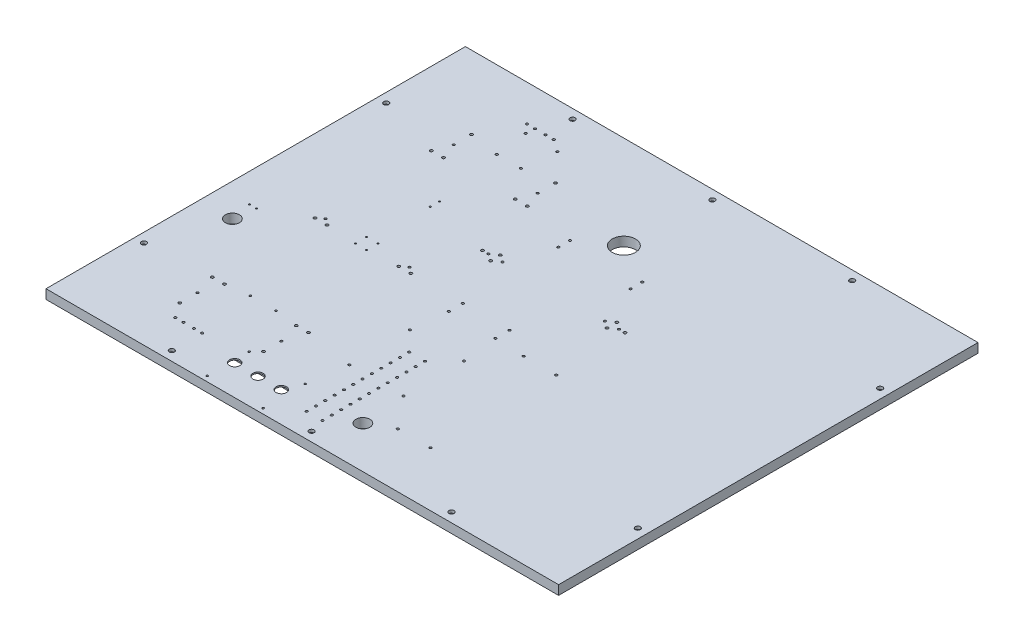
SolidWorks part; units mm, degrees
material "S45C表面镀硬铬"
ref_plane "前基準面" through (0, 0, 0) normal (0, 0, 1) x (1, 0, 0)
ref_plane "上基準面" through (0, 0, 0) normal (0, 1, 0) x (1, 0, 0)
ref_plane "右基準面" through (0, 0, 0) normal (1, 0, 0) x (0, 0, -1)
sketch "草图1" plane through (0, 0, 0) normal (0, 1, 0) x (1, 0, 0)
  line L1 (0, 0) -> (1100, 0)
  line L2 (0, 0) -> (0, 900)
  line L3 (0, 900) -> (1100, 900)
  line L4 (1100, 0) -> (1100, 900)
  dimension "D1" = 1100
  dimension "D2" = 900
extrude "凸台-拉伸1" add sketch "草图1" against normal blind 20
hole_wizard "M6 六角凹头螺钉的柱形沉头孔1" positions "草图3" profile "草图2" counterbore size "M6" standard "ISO" end condition through all
sketch "草图3" plane through (0, 0, 0) normal (0, 1, 0) x (-1, 0, 0)
  line L0 (0, -450) -> (-1100, -450) construction
  line L1 (0, -900) -> (0, 0) construction
  line L2 (-1100, 0) -> (-1100, -900) construction
  line L3 (-550, -900) -> (-550, 0) construction
  line L4 (-1100, -900) -> (0, -900) construction
  line L5 (0, 0) -> (-1100, 0) construction
  point P0 (-250, -20)
  point P1 (-550, -20)
  point P3 (-850, -20)
  point P5 (-1080, -190)
  point P7 (-1080, -710)
  point P9 (-850, -880)
  point P11 (-550, -880)
  point P13 (-250, -880)
  point P15 (-20, -710)
  point P17 (-20, -190)
  dimension "D1" = 600
  dimension "D2" = 20
  dimension "D3" = 20
  dimension "D4" = 520
sketch "草图2" plane through (250, 0, -20) normal (1, 0, 0) x (0, 0, 1)
  line L0 (0, 0) -> (0, 20)
  line L1 (0, 20) -> (3.5, 20)
  line L3 (3.5, 20) -> (3.5, 6)
  line L4 (3.5, 6) -> (5.5, 6)
  line L5 (5.5, 6) -> (5.5, 0)
  line L7 (5.5, 0) -> (0, 0)
  line L11 (0, -6.35) -> (0, 107.95) construction
  dimension "通孔孔直径" = 7
  dimension "通孔孔深度" = 20
  dimension "柱形沉头孔直径" = 11
  dimension "柱形沉头孔深度" = 6
hole_wizard "M4 螺纹孔1" positions "草图5" profile "草图4" tap size "M4" standard "ISO"
sketch "草图5" plane through (0, 0, 0) normal (0, 1, 0) x (-1, 0, 0)
  line L0 (0, -900) -> (0, 0) construction
  line L1 (-1100, -900) -> (0, -900) construction
  point P0 (-260, -584.5)
  point P1 (-260, -564.5)
  dimension "D1" = 20
  dimension "D2" = 260
  dimension "D3" = 315.5
sketch "草图4" plane through (260, 0, -584.5) normal (1, 0, 0) x (0, 0, 1)
  line L0 (0, 0) -> (0, 11.0914)
  line L1 (0, 11.0914) -> (1.65, 10.1)
  line L2 (1.65, 10.1) -> (1.65, 0)
  line L5 (1.65, 0) -> (0, 0)
  line L10 (0, 11.0914) -> (-1.65, 10.1) construction
  line L11 (0, -6.35) -> (0, 107.95) construction
  dimension "螺纹孔钻头直径" = 3.3
  dimension "螺纹孔钻头深度" = 10.1
  dimension "导头角度" = 118
cosmetic thread "孔螺蚊线1" parameters "D1"=8, "D2"=4
cosmetic thread "孔螺蚊线2" parameters "D1"=8, "D2"=4
hole_wizard "M4 螺纹孔2" positions "草图7" profile "草图6" tap size "M4" standard "ISO"
sketch "草图7" plane through (0, 0, 0) normal (0, 1, 0) x (-1, 0, 0)
  line L0 (0, -900) -> (0, 0) construction
  line L1 (0, 0) -> (-1100, 0) construction
  point P0 (-272, -440)
  point P1 (-248, -440)
  point P3 (-272, -416)
  point P5 (-248, -416)
  dimension "D1" = 24
  dimension "D2" = 24
  dimension "D3" = 248
  dimension "D4" = 416
sketch "草图6" plane through (272, 0, -440) normal (1, 0, 0) x (0, 0, 1)
  line L0 (0, 0) -> (0, 11.0914)
  line L1 (0, 11.0914) -> (1.65, 10.1)
  line L2 (1.65, 10.1) -> (1.65, 0)
  line L5 (1.65, 0) -> (0, 0)
  line L10 (0, 11.0914) -> (-1.65, 10.1) construction
  line L11 (0, -6.35) -> (0, 107.95) construction
  dimension "螺纹孔钻头直径" = 3.3
  dimension "螺纹孔钻头深度" = 10.1
  dimension "导头角度" = 118
cosmetic thread "孔螺蚊线3" parameters "D1"=8, "D2"=4
cosmetic thread "孔螺蚊线4" parameters "D1"=8, "D2"=4
cosmetic thread "孔螺蚊线5" parameters "D1"=8, "D2"=4
cosmetic thread "孔螺蚊线6" parameters "D1"=8, "D2"=4
sketch "草图8" plane through (0, 0, 0) normal (0, 1, 0) x (1, 0, 0)
  line L0 (0, 900) -> (0, 0) construction
  line L1 (0, 0) -> (1100, 0) construction
  circle A0 centre (340, 65) radius 11
  circle A1 centre (390, 65) radius 11
  circle A2 centre (440, 65) radius 11
  dimension "D1" = 22
  dimension "D2" = 340
  dimension "D3" = 65
  dimension "D4" = 50
  dimension "D5" = 50
extrude "切除-拉伸1" cut sketch "草图8" against normal through all
sketch "草图9" plane through (0, -20, 0) normal (0, -1, 0) x (1, 0, 0)
  line L0 (340, -65) -> (440, -65) construction
  line L1 (310, -40) -> (470, -40)
  line L2 (310, -40) -> (310, -90)
  line L3 (310, -90) -> (470, -90)
  line L4 (470, -40) -> (470, -90)
  line L5 (390, -65) -> (390, -147.6658) construction
  dimension "D1" = 50
  dimension "D2" = 160
extrude "切除-拉伸2" cut sketch "草图9" against normal blind 17
fillet "圆角1" radius 8 4 edges at (470, -11.5, -40) (470, -11.5, -90) (310, -11.5, -90) (310, -11.5, -40)
hole_wizard "M6 螺纹孔1" positions "草图11" profile "草图10" tap size "M6" standard "ISO"
sketch "草图11" plane through (0, 0, 0) normal (0, 1, 0) x (-1, 0, 0)
  point P1 (-210, -85)
  point P4 (-250, -85)
  point P8 (-170, -155)
  point P11 (-170, -430)
  point P14 (-170, -705)
  point P17 (-210, -822)
  point P20 (-250, -822)
  point P23 (-350, -155)
  point P26 (-350, -430)
  point P29 (-350, -705)
  point P32 (-472.5, -652)
  point P35 (-472.5, -627)
  point P38 (-440, -539.5)
  point P41 (-410, -539.5)
  point P44 (-690, -539.5)
  point P47 (-660, -539.5)
  point P50 (-627.5, -627)
  point P53 (-627.5, -652)
  dimension "D1" = 40
sketch "草图10" plane through (210, 0, -85) normal (1, 0, 0) x (0, 0, 1)
  line L0 (0, 0) -> (0, 16.5022)
  line L1 (0, 16.5022) -> (2.5, 15)
  line L2 (2.5, 15) -> (2.5, 0)
  line L5 (2.5, 0) -> (0, 0)
  line L10 (0, 16.5022) -> (-2.5, 15) construction
  line L11 (0, -6.35) -> (0, 107.95) construction
  dimension "螺纹孔钻头直径" = 5
  dimension "螺纹孔钻头深度" = 15
  dimension "导头角度" = 118
cosmetic thread "孔螺蚊线7" parameters "D1"=12, "D2"=6
cosmetic thread "孔螺蚊线8" parameters "D1"=12, "D2"=6
cosmetic thread "孔螺蚊线9" parameters "D1"=12, "D2"=6
cosmetic thread "孔螺蚊线10" parameters "D1"=12, "D2"=6
cosmetic thread "孔螺蚊线11" parameters "D1"=12, "D2"=6
cosmetic thread "孔螺蚊线12" parameters "D1"=12, "D2"=6
cosmetic thread "孔螺蚊线13" parameters "D1"=12, "D2"=6
cosmetic thread "孔螺蚊线14" parameters "D1"=12, "D2"=6
cosmetic thread "孔螺蚊线15" parameters "D1"=12, "D2"=6
cosmetic thread "孔螺蚊线16" parameters "D1"=12, "D2"=6
cosmetic thread "孔螺蚊线17" parameters "D1"=12, "D2"=6
cosmetic thread "孔螺蚊线18" parameters "D1"=12, "D2"=6
cosmetic thread "孔螺蚊线19" parameters "D1"=12, "D2"=6
cosmetic thread "孔螺蚊线20" parameters "D1"=12, "D2"=6
cosmetic thread "孔螺蚊线21" parameters "D1"=12, "D2"=6
cosmetic thread "孔螺蚊线22" parameters "D1"=12, "D2"=6
cosmetic thread "孔螺蚊线23" parameters "D1"=12, "D2"=6
cosmetic thread "孔螺蚊线24" parameters "D1"=12, "D2"=6
hole_wizard "M6 螺纹孔2" positions "草图13" profile "草图12" tap size "M6" standard "ISO"
sketch "草图13" plane through (0, 0, 0) normal (0, 1, 0) x (-1, 0, 0)
  line L0 (0, 0) -> (-1100, 0) construction
  line L1 (-1100, 0) -> (-1100, -900) construction
  point P0 (-638, -387)
  point P1 (-638, -117)
  point P3 (-708, -387)
  point P5 (-708, -117)
  dimension "D1" = 117
  dimension "D2" = 70
  dimension "D3" = 270
  dimension "D4" = 392
sketch "草图12" plane through (638, 0, -387) normal (1, 0, 0) x (0, 0, 1)
  line L0 (0, 0) -> (0, 16.5022)
  line L1 (0, 16.5022) -> (2.5, 15)
  line L2 (2.5, 15) -> (2.5, 0)
  line L5 (2.5, 0) -> (0, 0)
  line L10 (0, 16.5022) -> (-2.5, 15) construction
  line L11 (0, -6.35) -> (0, 107.95) construction
  dimension "螺纹孔钻头直径" = 5
  dimension "螺纹孔钻头深度" = 15
  dimension "导头角度" = 118
cosmetic thread "孔螺蚊线25" parameters "D1"=12, "D2"=6
cosmetic thread "孔螺蚊线26" parameters "D1"=12, "D2"=6
cosmetic thread "孔螺蚊线27" parameters "D1"=12, "D2"=6
cosmetic thread "孔螺蚊线28" parameters "D1"=12, "D2"=6
hole_wizard "M6 螺纹孔3" positions "草图15" profile "草图14" tap size "M6" standard "ISO"
sketch "草图15" plane through (0, 0, 0) normal (0, 1, 0) x (-1, 0, 0)
  line L0 (-1100, 0) -> (-1100, -900) construction
  line L1 (0, 0) -> (-1100, 0) construction
  point P0 (-474.5, -420)
  point P1 (-574.5, -420)
  point P3 (-574.5, -390)
  point P5 (-474.5, -390)
  dimension "D1" = 100
  dimension "D2" = 30
  dimension "D3" = 525.5
  dimension "D4" = 390
sketch "草图14" plane through (474.5, 0, -420) normal (1, 0, 0) x (0, 0, 1)
  line L0 (0, 0) -> (0, 16.5022)
  line L1 (0, 16.5022) -> (2.5, 15)
  line L2 (2.5, 15) -> (2.5, 0)
  line L5 (2.5, 0) -> (0, 0)
  line L10 (0, 16.5022) -> (-2.5, 15) construction
  line L11 (0, -6.35) -> (0, 107.95) construction
  dimension "螺纹孔钻头直径" = 5
  dimension "螺纹孔钻头深度" = 15
  dimension "导头角度" = 118
cosmetic thread "孔螺蚊线29" parameters "D1"=12, "D2"=6
cosmetic thread "孔螺蚊线30" parameters "D1"=12, "D2"=6
cosmetic thread "孔螺蚊线31" parameters "D1"=12, "D2"=6
cosmetic thread "孔螺蚊线32" parameters "D1"=12, "D2"=6
hole_wizard "M6 螺纹孔4" positions "草图17" profile "草图16" tap size "M6" standard "ISO"
sketch "草图17" plane through (0, 0, 0) normal (0, 1, 0) x (-1, 0, 0)
  line L0 (-574.5, -390) -> (-474.5, -390) construction
  line L1 (-524.5, -390) -> (-524.5, -255.0909) construction
  point P0 (-507.5, -271.8614)
  point P1 (-541.5, -271.8614)
  dimension "D1" = 34
sketch "草图16" plane through (507.5, 0, -271.8614) normal (1, 0, 0) x (0, 0, 1)
  line L0 (0, 0) -> (0, 16.5022)
  line L1 (0, 16.5022) -> (2.5, 15)
  line L2 (2.5, 15) -> (2.5, 0)
  line L5 (2.5, 0) -> (0, 0)
  line L10 (0, 16.5022) -> (-2.5, 15) construction
  line L11 (0, -6.35) -> (0, 107.95) construction
  dimension "螺纹孔钻头直径" = 5
  dimension "螺纹孔钻头深度" = 15
  dimension "导头角度" = 118
cosmetic thread "孔螺蚊线33" parameters "D1"=12, "D2"=6
cosmetic thread "孔螺蚊线34" parameters "D1"=12, "D2"=6
pattern_linear "阵列(线性)1" count 12 spacing 20 along (0, 0, 1) of "M6 螺纹孔4"
sketch "草图18" plane through (0, 0, 0) normal (0, 1, 0) x (1, 0, 0)
  line L0 (0, 0) -> (1100, 0) construction
  line L1 (1100, 0) -> (1100, 900) construction
  line L2 (1100, 900) -> (0, 900) construction
  line L3 (0, 900) -> (0, 0) construction
  circle A0 centre (540, 700) radius 25
  circle A1 centre (70, 330) radius 15
  circle A2 centre (590, 90) radius 15
  dimension "D1" = 50
  dimension "D2" = 30
  dimension "D3" = 30
  dimension "D4" = 90
  dimension "D5" = 510
  dimension "D6" = 200
  dimension "D7" = 560
  dimension "D8" = 70
  dimension "D9" = 570
extrude "切除-拉伸3" cut sketch "草图18" against normal through all
hole_wizard "M6 螺纹孔5" positions "草图20" profile "草图19" tap size "M6" standard "ISO"
sketch "草图20" plane through (0, 0, 0) normal (0, 1, 0) x (-1, 0, 0)
  line L0 (0, 0) -> (-1100, 0) construction
  line L1 (-1100, 0) -> (-1100, -900) construction
  point P0 (-467, -314)
  point P1 (-467, -184)
  point P3 (-583, -184)
  point P5 (-583, -314)
  dimension "D1" = 130
  dimension "D2" = 116
  dimension "D3" = 184
  dimension "D4" = 517
sketch "草图19" plane through (467, 0, -314) normal (1, 0, 0) x (0, 0, 1)
  line L0 (0, 0) -> (0, 16.5022)
  line L1 (0, 16.5022) -> (2.5, 15)
  line L2 (2.5, 15) -> (2.5, 0)
  line L5 (2.5, 0) -> (0, 0)
  line L10 (0, 16.5022) -> (-2.5, 15) construction
  line L11 (0, -6.35) -> (0, 107.95) construction
  dimension "螺纹孔钻头直径" = 5
  dimension "螺纹孔钻头深度" = 15
  dimension "导头角度" = 118
cosmetic thread "孔螺蚊线35" parameters "D1"=12, "D2"=6
cosmetic thread "孔螺蚊线36" parameters "D1"=12, "D2"=6
cosmetic thread "孔螺蚊线37" parameters "D1"=12, "D2"=6
cosmetic thread "孔螺蚊线38" parameters "D1"=12, "D2"=6
sketch "草图21" plane through (0, 0, 0) normal (0, 1, 0) x (1, 0, 0)
  line L0 (0, 0) -> (1100, 0) construction
  line L1 (0, 900) -> (0, 0) construction
  circle A0 centre (170, 117) radius 3
  circle A1 centre (350, 117) radius 3
  circle A2 centre (157, 200) radius 3
  circle A3 centre (183, 200) radius 3
  circle A4 centre (337, 200) radius 3
  circle A5 centre (363, 200) radius 3
  circle A6 centre (157, 420) radius 3
  circle A7 centre (183, 420) radius 3
  circle A8 centre (337, 420) radius 3
  circle A9 centre (363, 420) radius 3
  circle A10 centre (157, 670) radius 3
  circle A11 centre (183, 670) radius 3
  circle A12 centre (337, 670) radius 3
  circle A13 centre (363, 670) radius 3
  circle A14 centre (170, 743) radius 3
  circle A15 centre (350, 743) radius 3
  circle A16 centre (397, 539.5) radius 3
  circle A17 centre (425, 529) radius 3
  circle A18 centre (675, 529) radius 3
  circle A19 centre (425, 550) radius 3
  circle A20 centre (675, 550) radius 3
  circle A21 centre (703, 539.5) radius 3
  dimension "D1" = 6
  dimension "D2" = 117
  dimension "D3" = 170
  dimension "D5" = 157
  dimension "D6" = 183
  dimension "D7" = 200
  dimension "D8" = 337
  dimension "D14" = 529
  dimension "D15" = 539.5
  dimension "D16" = 425
  dimension "D17" = 21
  dimension "D18" = 250
  dimension "D19" = 306
  dimension "D4" = 350
  dimension "D9" = 363
  dimension "D10" = 420
  dimension "D11" = 670
  dimension "D12" = 743
  dimension "D13" = 397
extrude "切除-拉伸4" cut sketch "草图21" against normal through all
hole_wizard "M4 螺纹孔3" positions "草图23" profile "草图22" tap size "M4" standard "ISO"
sketch "草图23" plane through (0, 0, 0) normal (0, 1, 0) x (-1, 0, 0)
  line L0 (0, -900) -> (0, 0) construction
  line L1 (0, 0) -> (-1100, 0) construction
  point P0 (-61.5, -375)
  point P1 (-76.5, -375)
  dimension "D1" = 15
  dimension "D2" = 61.5
  dimension "D3" = 375
sketch "草图22" plane through (61.5, 0, -375) normal (1, 0, 0) x (0, 0, 1)
  line L0 (0, 0) -> (0, 11.0914)
  line L1 (0, 11.0914) -> (1.65, 10.1)
  line L2 (1.65, 10.1) -> (1.65, 0)
  line L5 (1.65, 0) -> (0, 0)
  line L10 (0, 11.0914) -> (-1.65, 10.1) construction
  line L11 (0, -6.35) -> (0, 107.95) construction
  dimension "螺纹孔钻头直径" = 3.3
  dimension "螺纹孔钻头深度" = 10.1
  dimension "导头角度" = 118
cosmetic thread "孔螺蚊线39" parameters "D1"=8, "D2"=4
cosmetic thread "孔螺蚊线40" parameters "D1"=8, "D2"=4
hole_wizard "M6 螺纹孔6" positions "草图25" profile "草图24" tap size "M6" standard "ISO"
sketch "草图25" plane through (0, 0, 0) normal (0, 1, 0) x (-1, 0, 0)
  point P0 (-192.5, -85)
  point P1 (-232.5, -85)
sketch "草图24" plane through (192.5, 0, -85) normal (1, 0, 0) x (0, 0, 1)
  line L0 (0, 0) -> (0, 16.5022)
  line L1 (0, 16.5022) -> (2.5, 15)
  line L2 (2.5, 15) -> (2.5, 0)
  line L5 (2.5, 0) -> (0, 0)
  line L10 (0, 16.5022) -> (-2.5, 15) construction
  line L11 (0, -6.35) -> (0, 107.95) construction
  dimension "螺纹孔钻头直径" = 5
  dimension "螺纹孔钻头深度" = 15
  dimension "导头角度" = 118
cosmetic thread "孔螺蚊线41" parameters "D1"=12, "D2"=6
cosmetic thread "孔螺蚊线42" parameters "D1"=12, "D2"=6
hole_wizard "M5 螺纹孔1" positions "草图27" profile "草图26" tap size "M5" standard "ISO"
sketch "草图27" plane through (0, 0, 0) normal (0, 1, 0) x (-1, 0, 0)
  point P1 (-335, -11)
  point P4 (-455, -11)
  point P7 (-455, -101)
  point P14 (-335, -101)
sketch "草图26" plane through (335, 0, -11) normal (1, 0, 0) x (0, 0, 1)
  line L0 (0, 0) -> (0, 13.6618)
  line L1 (0, 13.6618) -> (2.1, 12.4)
  line L2 (2.1, 12.4) -> (2.1, 0)
  line L5 (2.1, 0) -> (0, 0)
  line L10 (0, 13.6618) -> (-2.1, 12.4) construction
  line L11 (0, -6.35) -> (0, 107.95) construction
  dimension "螺纹孔钻头直径" = 4.2
  dimension "螺纹孔钻头深度" = 12.4
  dimension "导头角度" = 118
cosmetic thread "孔螺蚊线43" parameters "D1"=10, "D2"=5
cosmetic thread "孔螺蚊线44" parameters "D1"=10, "D2"=5
cosmetic thread "孔螺蚊线45" parameters "D1"=10, "D2"=5
cosmetic thread "孔螺蚊线46" parameters "D1"=10, "D2"=5
hole_wizard "M6 螺纹孔7" positions "草图29" profile "草图28" tap size "M6" standard "ISO"
sketch "草图29" plane through (0, 0, 0) normal (0, 1, 0) x (-1, 0, 0)
  point P1 (-267.5, -822)
  point P4 (-227.5, -822)
sketch "草图28" plane through (267.5, 0, -822) normal (1, 0, 0) x (0, 0, 1)
  line L0 (0, 0) -> (0, 16.5022)
  line L1 (0, 16.5022) -> (2.5, 15)
  line L2 (2.5, 15) -> (2.5, 0)
  line L5 (2.5, 0) -> (0, 0)
  line L10 (0, 16.5022) -> (-2.5, 15) construction
  line L11 (0, -6.35) -> (0, 107.95) construction
  dimension "螺纹孔钻头直径" = 5
  dimension "螺纹孔钻头深度" = 15
  dimension "导头角度" = 118
cosmetic thread "孔螺蚊线47" parameters "D1"=12, "D2"=6
cosmetic thread "孔螺蚊线48" parameters "D1"=12, "D2"=6
hole_wizard "M5 螺纹孔2" positions "草图31" profile "草图30" tap size "M5" standard "ISO"
sketch "草图31" plane through (0, 0, 0) normal (0, 1, 0) x (-1, 0, 0)
  point P0 (-232.5, -206)
  point P1 (-287.5, -206)
sketch "草图30" plane through (232.5, 0, -206) normal (1, 0, 0) x (0, 0, 1)
  line L0 (0, 0) -> (0, 13.6618)
  line L1 (0, 13.6618) -> (2.1, 12.4)
  line L2 (2.1, 12.4) -> (2.1, 0)
  line L5 (2.1, 0) -> (0, 0)
  line L10 (0, 13.6618) -> (-2.1, 12.4) construction
  line L11 (0, -6.35) -> (0, 107.95) construction
  dimension "螺纹孔钻头直径" = 4.2
  dimension "螺纹孔钻头深度" = 12.4
  dimension "导头角度" = 118
cosmetic thread "孔螺蚊线49" parameters "D1"=10, "D2"=5
cosmetic thread "孔螺蚊线50" parameters "D1"=10, "D2"=5
hole_wizard "M6 螺纹孔8" positions "草图33" profile "草图32" tap size "M6" standard "ISO"
sketch "草图33" plane through (0, 0, 0) normal (0, 1, 0) x (-1, 0, 0)
  point P0 (-226, -803.3)
  point P1 (-234, -733.3)
  point P4 (-286, -733.3)
  point P7 (-294, -803.3)
sketch "草图32" plane through (226, 0, -803.3) normal (1, 0, 0) x (0, 0, 1)
  line L0 (0, 0) -> (0, 16.5022)
  line L1 (0, 16.5022) -> (2.5, 15)
  line L2 (2.5, 15) -> (2.5, 0)
  line L5 (2.5, 0) -> (0, 0)
  line L10 (0, 16.5022) -> (-2.5, 15) construction
  line L11 (0, -6.35) -> (0, 107.95) construction
  dimension "螺纹孔钻头直径" = 5
  dimension "螺纹孔钻头深度" = 15
  dimension "导头角度" = 118
cosmetic thread "孔螺蚊线51" parameters "D1"=12, "D2"=6
cosmetic thread "孔螺蚊线52" parameters "D1"=12, "D2"=6
cosmetic thread "孔螺蚊线53" parameters "D1"=12, "D2"=6
cosmetic thread "孔螺蚊线54" parameters "D1"=12, "D2"=6
